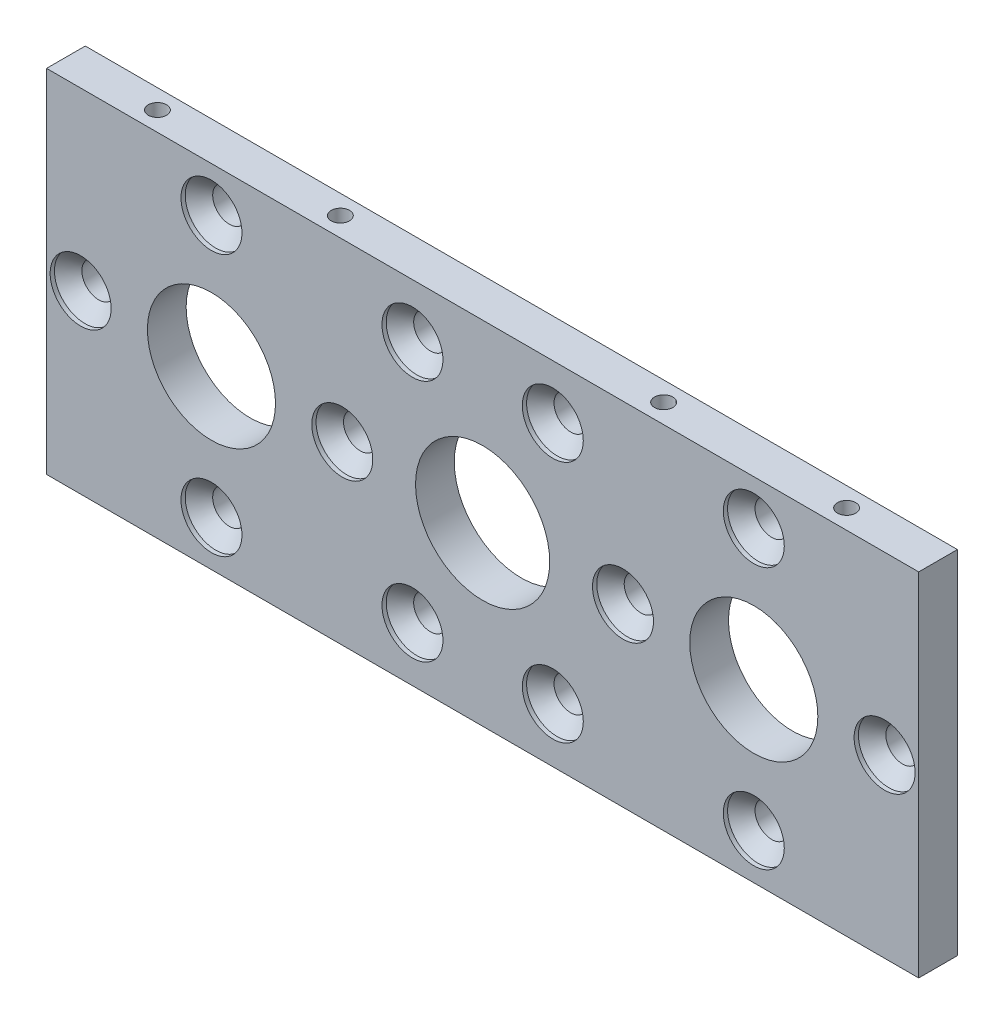
SolidWorks part; units mm, degrees
ref_plane "Plano frontal" through (0, 0, 0) normal (0, 0, 1) x (1, 0, 0)
ref_plane "Plano superior" through (0, 0, 0) normal (0, 1, 0) x (1, 0, 0)
ref_plane "Plano direito" through (0, 0, 0) normal (1, 0, 0) x (0, 0, -1)
sketch "Esboço1" plane through (0, 0, 0) normal (0, 0, 1) x (1, 0, 0)
  line L0 (71.505, 27.025) -> (-71.505, -27.025) construction
  line L1 (-71.505, 27.025) -> (71.505, 27.025)
  line L2 (-71.505, 27.025) -> (-71.505, -27.025)
  line L3 (-71.505, -27.025) -> (71.505, -27.025)
  line L4 (71.505, 27.025) -> (71.505, -27.025)
  dimension "D1" = 143.01
  dimension "D2" = 54.05
extrude "Ressalto-extrusão1" add sketch "Esboço1" along normal blind 6.35
sketch "Esboço2" plane through (0, 0, 0) normal (0, 0, -1) x (-1, 0, 0)
  circle A0 centre (-44.4631, 23.2919) radius 2.75
  circle A1 centre (-65.9131, 1.8419) radius 2.75
  circle A2 centre (-44.4631, -19.6081) radius 2.75
  circle A3 centre (-23.0131, 1.8419) radius 2.75
  circle A4 centre (-11.5056, 21.7734) radius 2.75
  circle A5 centre (11.5094, 21.7734) radius 2.75
  circle A6 centre (23.0169, 1.8419) radius 2.75
  circle A7 centre (11.5094, -18.0897) radius 2.75
  circle A8 centre (-11.5056, -18.0897) radius 2.75
  circle A9 centre (44.4669, -19.6081) radius 2.75
  circle A10 centre (65.9169, 1.8419) radius 2.75
  circle A11 centre (44.4669, 23.2919) radius 2.75
  dimension "D1" = 5.5
  dimension "D2" = 5.5
  dimension "D3" = 5.5
  dimension "D4" = 5.5
  dimension "D5" = 5.5
  dimension "D6" = 5.5
  dimension "D7" = 5.5
  dimension "D8" = 5.5
  dimension "D9" = 5.5
  dimension "D10" = 5.5
  dimension "D11" = 5.5
  dimension "D12" = 5.5
extrude "Corte-extrusão1" cut sketch "Esboço2" against normal blind 10
sketch "Esboço3" plane through (0, 0, 0) normal (0, 0, -1) x (-1, 0, 0)
  circle A0 centre (-44.4631, 1.8419) radius 10.5
  circle A1 centre (0.0019, 1.8419) radius 11
  circle A2 centre (44.4669, 1.8419) radius 10.5
  dimension "D1" = 22
  dimension "D2" = 21
  dimension "D3" = 21
extrude "Corte-extrusão2" cut sketch "Esboço3" against normal blind 10
sketch "Esboço4" plane through (0, 0, 0) normal (0, 0, 1) x (1, 0, 0)
  line L1 (-71.505, 27.025) -> (71.505, 27.025)
  line L2 (-71.505, 27.025) -> (-71.505, 30.645)
  line L3 (-71.505, 30.645) -> (71.505, 30.645)
  line L4 (71.505, 27.025) -> (71.505, 30.645)
  dimension "D1" = 143.01
  dimension "D2" = 3.62
extrude "Ressalto-extrusão2" add sketch "Esboço4" along normal blind 6.35
sketch "Esboço8" plane through (0, 30.645, 0) normal (0, 1, 0) x (1, 0, 0)
  line L0 (71.505, -3.175) -> (-71.505, -3.175) construction
  line L1 (71.505, -6.35) -> (71.505, 0) construction
  line L2 (-71.505, -6.35) -> (-71.505, 0) construction
  line L3 (0, 0) -> (0, -6.35) construction
  line L4 (71.505, 0) -> (-71.505, 0) construction
  line L5 (71.505, -6.35) -> (-71.505, -6.35) construction
  circle A0 centre (56.505, -3.175) radius 1.5
  circle A1 centre (26.505, -3.175) radius 1.5
  circle A2 centre (-26.505, -3.175) radius 1.5
  circle A3 centre (-56.505, -3.175) radius 1.5
  dimension "D1" = 3
  dimension "D2" = 3
  dimension "D3" = 15
  dimension "D4" = 30
extrude "Corte-extrusão3" cut sketch "Esboço8" against normal blind 15
sketch "Esboço9" plane through (0, 0, 6.35) normal (0, 0, 1) x (1, 0, 0)
  circle A0 centre (44.4631, -19.6081) radius 5
  circle A1 centre (65.9131, 1.8419) radius 5
  circle A2 centre (44.4631, 23.2919) radius 5
  circle A3 centre (23.0131, 1.8419) radius 5
  circle A4 centre (11.5056, -18.0897) radius 5
  circle A5 centre (11.5056, 21.7734) radius 5
  circle A6 centre (-11.5094, 21.7734) radius 5
  circle A7 centre (-23.0169, 1.8419) radius 5
  circle A8 centre (-11.5094, -18.0897) radius 5
  circle A9 centre (-44.4669, 23.2919) radius 5
  circle A10 centre (-65.9169, 1.8419) radius 5
  circle A11 centre (-44.4669, -19.6081) radius 5
  dimension "D1" = 10
  dimension "D2" = 10
  dimension "D3" = 10
  dimension "D4" = 10
  dimension "D5" = 10
  dimension "D6" = 10
  dimension "D7" = 10
  dimension "D8" = 10
  dimension "D9" = 10
  dimension "D10" = 10
  dimension "D11" = 10
  dimension "D12" = 10
extrude "Corte-extrusão4" cut sketch "Esboço9" against normal blind 0.7
sketch "Esboço12" plane through (0, 0, 5.65) normal (0, 0, 1) x (1, 0, 0)
  circle A0 centre (-65.9169, 1.8419) radius 5
  circle A1 centre (-44.4669, 23.2919) radius 5
  circle A2 centre (-23.0169, 1.8419) radius 5
  circle A3 centre (-11.5094, 21.7734) radius 5
  circle A4 centre (-44.4669, -19.6081) radius 5
  circle A5 centre (-11.5094, -18.0897) radius 5
  circle A6 centre (11.5056, -18.0897) radius 5
  circle A7 centre (44.4631, -19.6081) radius 5
  circle A8 centre (23.0131, 1.8419) radius 5
  circle A9 centre (65.9131, 1.8419) radius 5
  circle A10 centre (44.4631, 23.2919) radius 5
  circle A11 centre (11.5056, 21.7734) radius 5
extrude "Corte-extrusão5" cut sketch "Esboço12" against normal blind 2.5 draft 45
